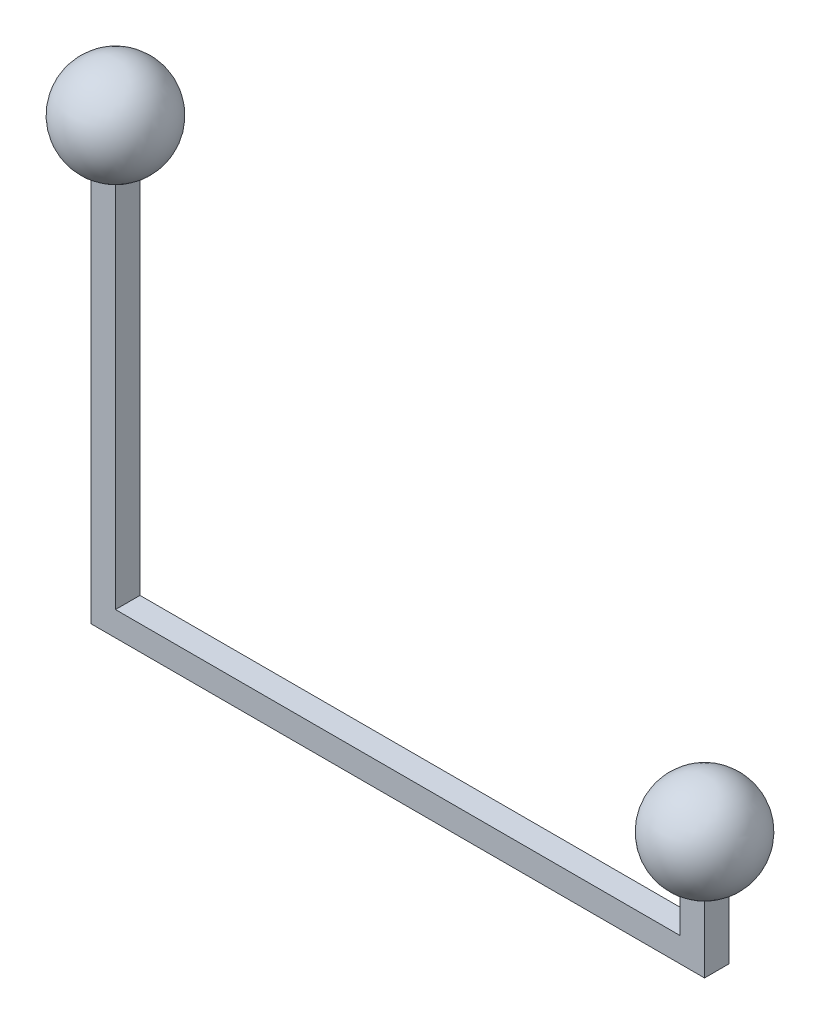
SolidWorks part; units mm, degrees
ref_plane "Front Plane" through (0, 0, 0) normal (0, 0, 1) x (1, 0, 0)
ref_plane "Top Plane" through (0, 0, 0) normal (0, 1, 0) x (1, 0, 0)
ref_plane "Right Plane" through (0, 0, 0) normal (1, 0, 0) x (0, 0, -1)
sketch "Sketch1" plane through (0, 0, 0) normal (0, 0, 1) x (1, 0, 0)
  line L0 (0, 0) -> (79.375, 0)
  line L1 (79.375, 0) -> (79.375, 8.639)
  line L2 (79.375, 8.639) -> (76.2, 8.639)
  line L3 (76.2, 8.639) -> (76.2, 3.175)
  line L4 (76.2, 3.175) -> (3.175, 3.175)
  line L5 (3.175, 3.175) -> (3.175, 50.8)
  line L6 (3.175, 50.8) -> (0, 50.8)
  line L7 (0, 50.8) -> (0, 0)
  line L8 (3.175, 50.8) -> (76.2, 8.639) construction
  dimension "D1" = 79.375
  dimension "D2" = 3.175
  dimension "D3" = 3.175
  dimension "D4" = 3.175
  dimension "D5" = 60
  dimension "D6" = 50.8
extrude "Boss-Extrude1" add sketch "Sketch1" along normal blind 3.175
ref_plane "Plane1" through (0, 0, 1.5875) normal (0, 0, 1) x (1, 0, 0)
sketch "Sketch2" plane through (0, 0, 1.5875) normal (0, 0, 1) x (1, 0, 0)
  line L1 (1.5875, 50.5984) -> (1.5875, 63.2984)
  arc A0 (1.5875, 50.5984) -> (1.5875, 63.2984) centre (1.5875, 56.9484) ccw
  dimension "D1" = 12.7
revolve "Revolve1" add sketch "Sketch2" angle 360 about L1
sketch "Sketch3" plane through (0, 0, 1.5875) normal (0, 0, 1) x (1, 0, 0)
  line L0 (77.7875, 21.1374) -> (77.7875, 8.4374)
  arc A0 (77.7875, 8.4374) -> (77.7875, 21.1374) centre (77.7875, 14.7874) ccw
  dimension "D1" = 12.7
revolve "Revolve2" add sketch "Sketch3" angle 360 about L0
